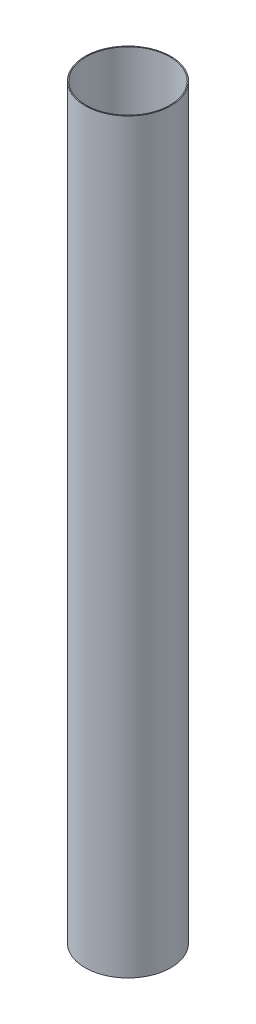
SolidWorks part; units mm, degrees
material "Hexcel AS4C (3000 Filaments)"
ref_plane "Front Plane" through (0, 0, 0) normal (0, 0, 1) x (1, 0, 0)
ref_plane "Top Plane" through (0, 0, 0) normal (0, 1, 0) x (1, 0, 0)
ref_plane "Right Plane" through (0, 0, 0) normal (1, 0, 0) x (0, 0, -1)
sketch "Sketch1" plane through (0, 0, 0) normal (0, 1, 0) x (1, 0, 0)
  circle A0 centre (0, 0) radius 87.5284
  circle A1 centre (0, 0) radius 85.6234
  dimension "D1" = 175.0568
  dimension "D2" = 171.2468
extrude "Boss-Extrude1" add sketch "Sketch1" along normal blind 1524
